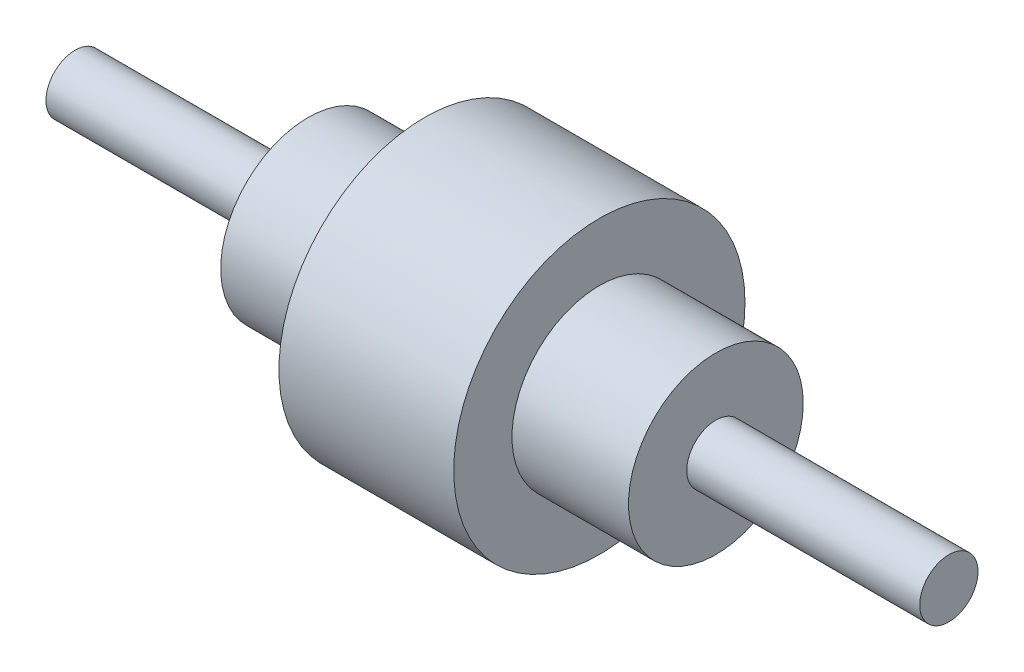
SolidWorks part; units mm, degrees
ref_plane "前基準面" through (0, 0, 0) normal (0, 0, 1) x (1, 0, 0)
ref_plane "上基準面" through (0, 0, 0) normal (0, 1, 0) x (1, 0, 0)
ref_plane "右基準面" through (0, 0, 0) normal (1, 0, 0) x (0, 0, -1)
ref_plane "平面1"
sketch "草圖1" plane through (0, 0, 0) normal (0, 0, 1) x (1, 0, 0)
  line L0 (100, 0) -> (180, 0)
  line L1 (180, 0) -> (180, 10)
  line L2 (180, 10) -> (100, 10)
  line L3 (100, 10) -> (100, 0)
  line L4 (0, 0) -> (-40, 0) construction
  line L5 (-40, 0) -> (-40, 10)
  line L6 (-40, 10) -> (-120, 10)
  line L7 (-120, 10) -> (-120, 0)
  line L8 (-120, 0) -> (-40, 0)
  line L9 (60, 0) -> (100, 0)
  line L10 (100, 0) -> (100, 30)
  line L11 (100, 30) -> (60, 30)
  line L12 (60, 30) -> (60, 0)
  line L13 (0, 0) -> (0, 30)
  line L14 (0, 30) -> (-40, 30)
  line L15 (-40, 30) -> (-40, 0)
  line L16 (-40, 0) -> (0, 0)
  line L17 (0, 0) -> (60, 0)
  line L18 (60, 0) -> (60, 50)
  line L19 (60, 50) -> (0, 50)
  line L20 (0, 50) -> (0, 0)
  dimension "D1" = 60
  dimension "D2" = 50
  dimension "D3" = 40
  dimension "D4" = 30
  dimension "D5" = 80
  dimension "D6" = 10
  dimension "D7" = 40
  dimension "D8" = 30
  dimension "D9" = 80
  dimension "D10" = 10
revolve "迴轉1" add sketch "草圖1" angle 360 about L4
